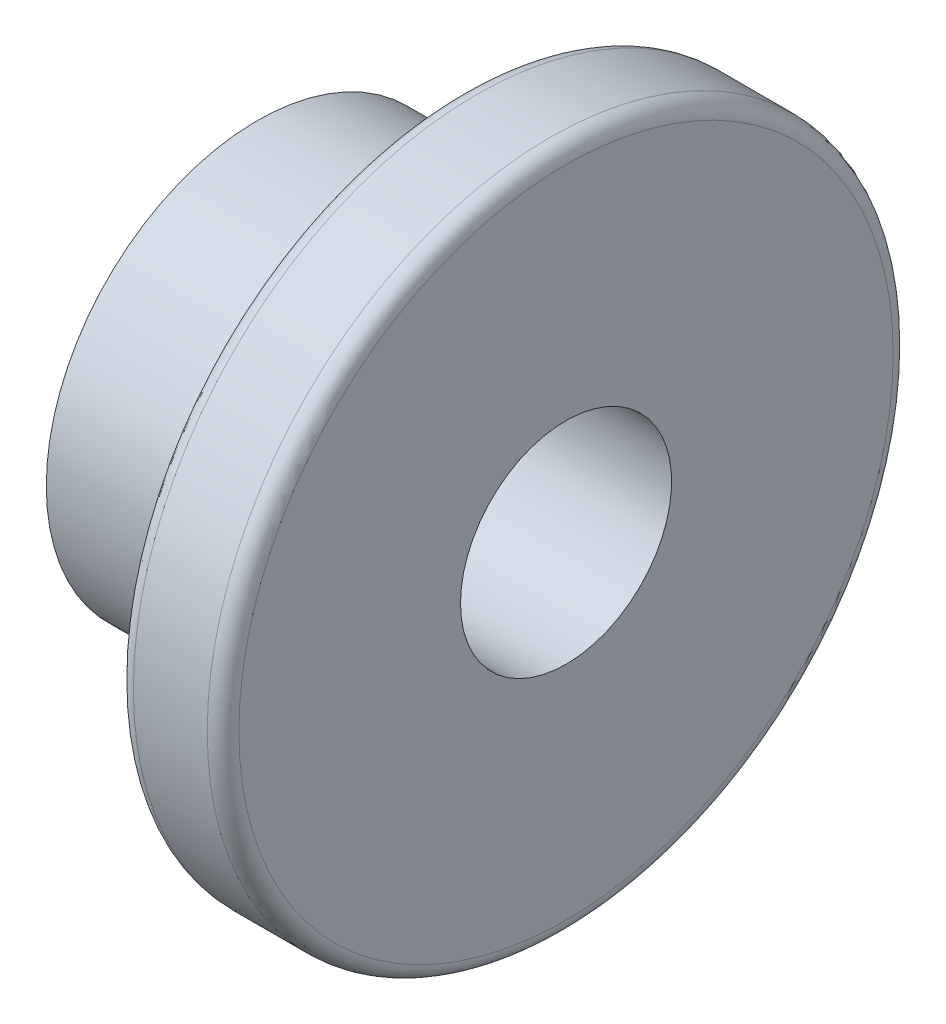
SolidWorks part; units mm, degrees
ref_plane "Plan de face" through (0, 0, 0) normal (0, 0, 1) x (1, 0, 0)
ref_plane "Plan de dessus" through (0, 0, 0) normal (0, 1, 0) x (1, 0, 0)
ref_plane "Plan de droite" through (0, 0, 0) normal (1, 0, 0) x (0, 0, -1)
sketch "Esquisse1" plane through (0, 0, 0) normal (0, 0, 1) x (1, 0, 0)
  line L0 (0, 0) -> (46.47, 0) construction
  line L1 (0, 4) -> (11.7, 4)
  line L2 (11.7, 4) -> (11.7, 13)
  line L3 (11.7, 13) -> (7.7, 13)
  line L4 (7.7, 13) -> (7.7, 8)
  line L5 (7.7, 8) -> (0, 8)
  line L6 (0, 8) -> (0, 4)
  dimension "D1" = 11.7
  dimension "D2" = 8
  dimension "D3" = 4
  dimension "D4" = 4
  dimension "D5" = 5
revolve "Révolution1" add sketch "Esquisse1" angle 360 about L0
fillet "Congé1" radius 0.6 2 edges at (11.7, 0, 13) (7.7, 0, 13)
